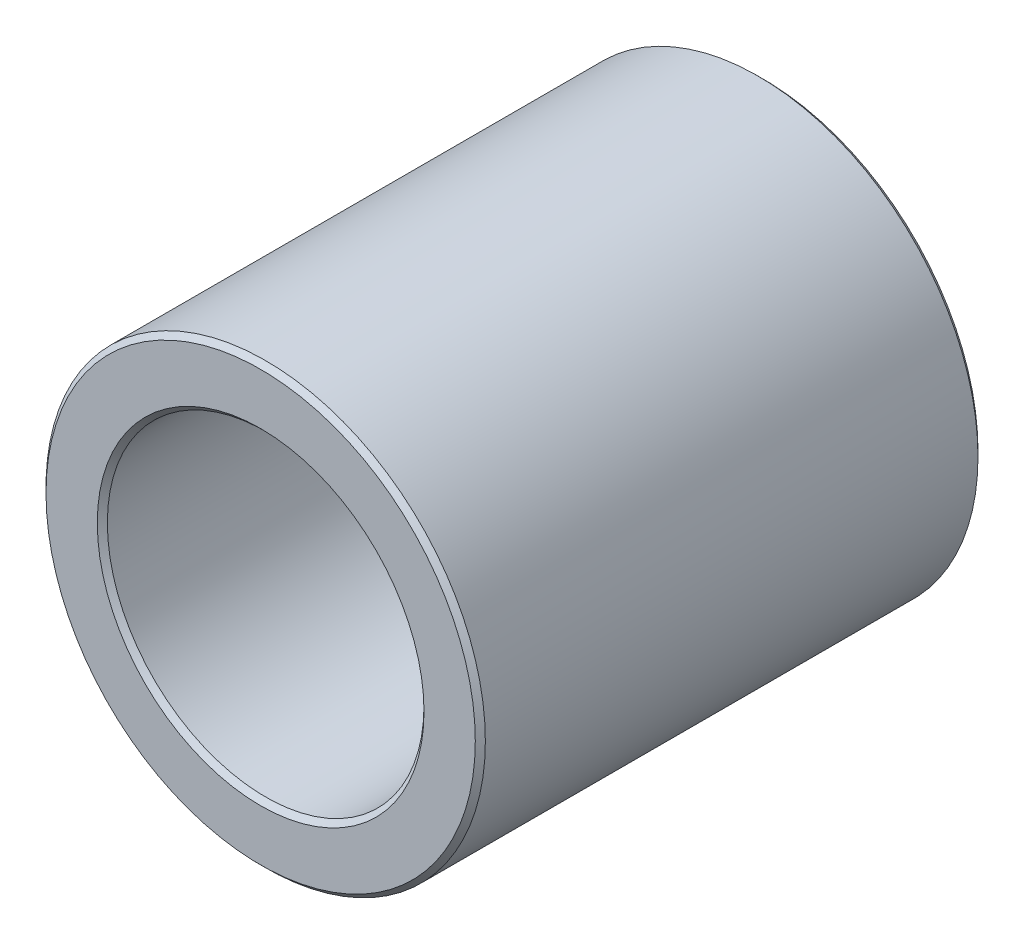
SolidWorks part; units mm, degrees
material "Hexcel AS4C (3000 Filaments)"
ref_plane "Front Plane" through (0, 0, 0) normal (0, 0, 1) x (1, 0, 0)
ref_plane "Top Plane" through (0, 0, 0) normal (0, 1, 0) x (1, 0, 0)
ref_plane "Right Plane" through (0, 0, 0) normal (1, 0, 0) x (0, 0, -1)
sketch "Sketch1" plane through (0, 0, 0) normal (0, 0, 1) x (1, 0, 0)
  circle A0 centre (0, 0) radius 5.5499
  circle A1 centre (0, 0) radius 4
  dimension "D1" = 8
  dimension "D2" = 11.0998
extrude "Boss-Extrude1" add sketch "Sketch1" along normal blind 12.7
chamfer "Chamfer1" distance 0.127 angle 45 4 edges at (4, 0, 0) (4, 0, 12.7) (5.5499, 0, 0) (5.5499, 0, 12.7)
equation "\"D1@Sketch1\"=8mm"
